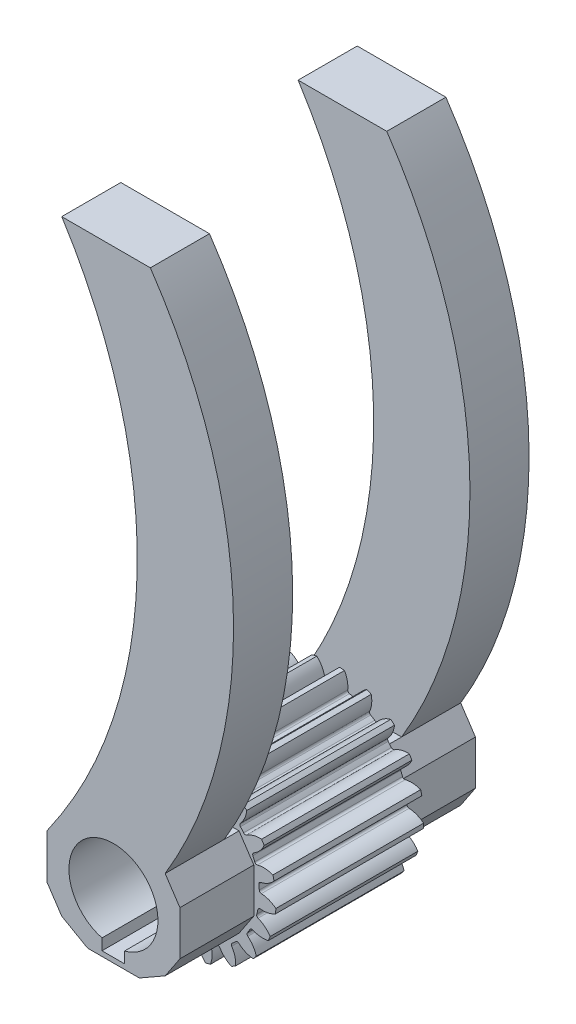
SolidWorks part; units mm, degrees
ref_plane "Alzado" through (0, 0, 0) normal (0, 0, 1) x (1, 0, 0)
ref_plane "Planta" through (0, 0, 0) normal (0, 1, 0) x (1, 0, 0)
ref_plane "Vista lateral" through (0, 0, 0) normal (1, 0, 0) x (0, 0, -1)
sketch "Croquis1" plane through (0, 0, 0) normal (0, 0, 1) x (1, 0, 0)
  circle A0 centre (0, 0) radius 12
  dimension "D1" = 24
extrude "Saliente-Extruir1" add sketch "Croquis1" along normal blind 20
sketch "Croquis2" plane through (0, 0, 20) normal (0, 0, 1) x (1, 0, 0)
  arc A0 (0.6093, 11.9845) -> (-2.4773, 11.7415) centre (0, 0) ccw
  arc A2 (-0.4361, 9.7402) -> (-1.0936, 9.6885) centre (0, 0) ccw
  arc A3 (0.6093, 11.9845) -> (-0.15, 10.0229) centre (3.2647, 9.8289) ccw
  arc A4 (-2.4773, 11.7415) -> (-1.4204, 9.9229) centre (-4.7627, 9.1969) cw
  arc A5 (-0.15, 10.0229) -> (-0.4361, 9.7402) centre (-0.4495, 10.0399) cw
  arc A6 (-1.4204, 9.9229) -> (-1.0936, 9.6885) centre (-1.1272, 9.9866) ccw
  dimension "D1" = 24
  dimension "D2" = 0.3
  dimension "D3" = 19.5
extrude "Cortar-Extruir1" cut sketch "Croquis2" against normal through all
pattern_circular "MatrizC2" count 20 every 18 about axis through (0, 0, 0) along (0, 0, 1) of "Cortar-Extruir1"
ref_plane "Plano1" through (0, 0, 10) normal (0, 0, 1) x (1, 0, 0)
sketch "Croquis4" plane through (0, 0, 10) normal (0, 0, 1) x (1, 0, 0)
  line L0 (-7, -6) -> (-3.5, -8)
  line L3 (-7, 6) -> (7, 6)
  line L5 (-7, -6) -> (7, 6) construction
  line L6 (-7, 6) -> (7, -6) construction
  line L7 (-3.5, -8) -> (3.5, -8)
  line L8 (3.5, -8) -> (7, -6)
  line L9 (-7, 6) -> (-9, 3)
  line L10 (-9, 3) -> (-9, -3)
  line L11 (-9, -3) -> (-7, -6)
  line L12 (7, 6) -> (9, 3)
  line L13 (9, 3) -> (9, -3)
  line L14 (9, -3) -> (7, -6)
  point P0 (0, 0)
  dimension "D1" = 14
  dimension "D2" = 12
  dimension "D3" = 6
  dimension "D4" = 7
  dimension "D5" = 2
  dimension "D6" = 2
  dimension "D7" = 2
  dimension "D8" = 2
  dimension "D9" = 3
  dimension "D10" = 3.5
  dimension "D11" = 6
  dimension "D12" = 3
  dimension "D13" = 2
  dimension "D14" = 2
extrude "Saliente-Extruir2" add sketch "Croquis4" along normal mid plane 40
sketch "Croquis6" plane through (0, 0, 30) normal (0, 0, 1) x (1, 0, 0)
  line L0 (-7, 6) -> (-7, 76) construction
  line L1 (-7, 76) -> (5, 76)
  line L2 (-7, 6) -> (7, 6)
  arc A0 (-7, 76) -> (-7, 6) centre (-61.7723, 41) cw
  arc A1 (5, 76) -> (7, 6) centre (-48.7408, 39.436) cw
  dimension "D2" = 65
  dimension "D4" = 65
  dimension "D1" = 70
  dimension "D3" = 12
extrude "Saliente-Extruir3" add sketch "Croquis6" against normal blind 8
mirror "Simetría1" about plane through (0, 0, 10) normal (0, 0, 1) of "Saliente-Extruir3"
sketch "Croquis7" plane through (0, 0, 30) normal (0, 0, 1) x (1, 0, 0)
  line L0 (0, 0) -> (-6.025, 0) construction
  line L2 (1.5, -5.8353) -> (1.5, -7.3353)
  line L9 (1.5, -7.3353) -> (-1.55, -7.3353)
  line L10 (-1.55, -7.3353) -> (-1.55, -5.8222)
  line L12 (0, 0) -> (0, -8) construction
  line L13 (-3.5, -8) -> (3.5, -8) construction
  arc A0 (1.5, -5.8353) -> (-1.55, -5.8222) centre (0, 0) ccw
  dimension "D1" = 12.05
  dimension "D2" = 3.05
  dimension "D3" = 1.5
  dimension "D4" = 1.5
extrude "Cortar-Extruir2" cut sketch "Croquis7" against normal through all
sketch "Sketch2" plane through (0, 0, -10) normal (0, 0, -1) x (-1, 0, 0)
  line L0 (-7, 6) -> (3.8428, 11.5182)
  line L1 (3.8428, 11.5182) -> (7, 76)
  line L2 (7, 76) -> (-16.2327, 76)
  line L3 (-16.2327, 76) -> (-16.2592, 39.436)
  line L4 (-16.2592, 39.436) -> (-16.2592, 6.1885)
  line L5 (-16.2592, 6.1885) -> (-7, 6)
  arc A1 (7, 76) -> (7, 6) centre (61.7723, 41) ccw construction
  arc A2 (-5, 76) -> (-7, 6) centre (48.7408, 39.436) ccw construction
